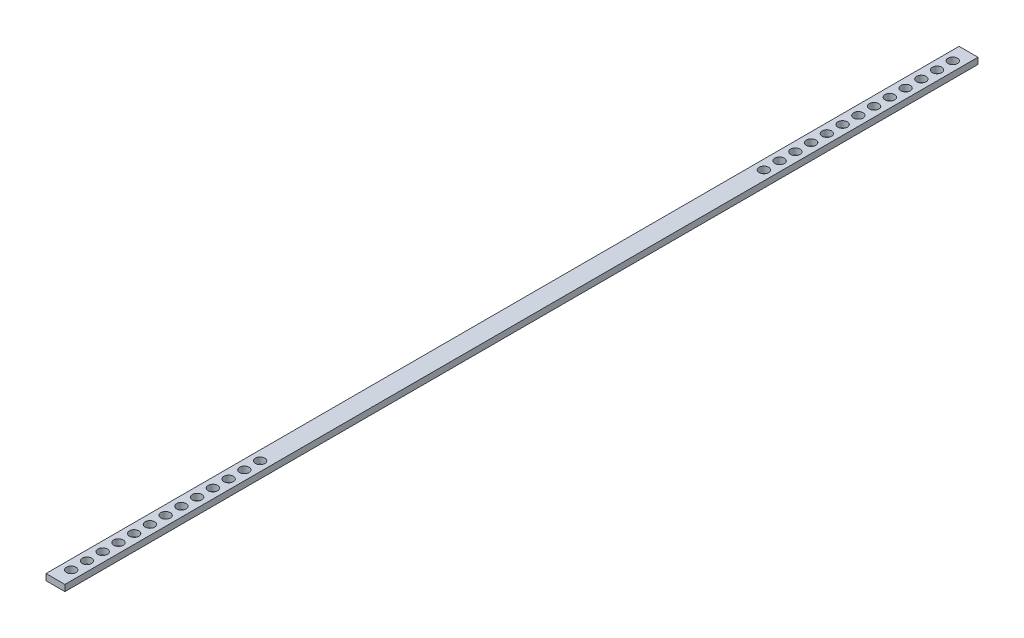
SolidWorks part; units mm, degrees
ref_plane "Ebene vorne" through (0, 0, 0) normal (0, 0, 1) x (1, 0, 0)
ref_plane "Ebene oben" through (0, 0, 0) normal (0, 1, 0) x (1, 0, 0)
ref_plane "Ebene rechts" through (0, 0, 0) normal (1, 0, 0) x (0, 0, -1)
sketch "Skizze1" plane through (0, 0, 0) normal (0, 0, 1) x (1, 0, 0)
  line L1 (0, 0) -> (12, 0)
  line L2 (0, 0) -> (0, 4)
  line L3 (0, 4) -> (12, 4)
  line L4 (12, 0) -> (12, 4)
  dimension "D1" = 12
  dimension "D2" = 4
extrude "Aufsatz-Linear austragen1" add sketch "Skizze1" along normal blind 580
sketch "Skizze2" plane through (0, 4, 0) normal (0, 1, 0) x (1, 0, 0)
  line L0 (0, -290) -> (12, -290) construction
  line L1 (0, -580) -> (0, 0) construction
  line L2 (12, -580) -> (12, 0) construction
  line L3 (6, 0) -> (6, -10) construction
  line L4 (12, 0) -> (0, 0) construction
  line L5 (6, -10) -> (6, -20) construction
  line L6 (6, -20) -> (6, -30) construction
  line L7 (6, -30) -> (6, -40) construction
  line L8 (6, -40) -> (6, -50) construction
  line L9 (6, -50) -> (6, -60) construction
  line L10 (6, -60) -> (6, -70) construction
  line L11 (6, -70) -> (6, -80) construction
  line L12 (6, -80) -> (6, -90) construction
  line L13 (6, -90) -> (6, -100) construction
  line L14 (6, -100) -> (6, -110) construction
  line L15 (6, -110) -> (6, -120) construction
  line L16 (6, -120) -> (6, -130) construction
  line L17 (6, -460) -> (6, -450) construction
  line L18 (6, -470) -> (6, -460) construction
  line L19 (6, -480) -> (6, -470) construction
  line L20 (6, -490) -> (6, -480) construction
  line L21 (6, -500) -> (6, -490) construction
  line L22 (6, -510) -> (6, -500) construction
  line L23 (6, -520) -> (6, -510) construction
  line L24 (6, -530) -> (6, -520) construction
  line L25 (6, -540) -> (6, -530) construction
  line L26 (6, -550) -> (6, -540) construction
  line L27 (6, -560) -> (6, -550) construction
  line L28 (6, -570) -> (6, -560) construction
  line L29 (6, -580) -> (6, -570) construction
  circle A0 centre (6, -10) radius 3
  circle A1 centre (6, -20) radius 3
  circle A2 centre (6, -30) radius 3
  circle A3 centre (6, -40) radius 3
  circle A4 centre (6, -50) radius 3
  circle A5 centre (6, -60) radius 3
  circle A6 centre (6, -70) radius 3
  circle A7 centre (6, -80) radius 3
  circle A8 centre (6, -90) radius 3
  circle A9 centre (6, -100) radius 3
  circle A10 centre (6, -110) radius 3
  circle A11 centre (6, -120) radius 3
  circle A12 centre (6, -130) radius 3
  circle A13 centre (6, -450) radius 3
  circle A14 centre (6, -460) radius 3
  circle A15 centre (6, -470) radius 3
  circle A16 centre (6, -480) radius 3
  circle A17 centre (6, -490) radius 3
  circle A18 centre (6, -500) radius 3
  circle A19 centre (6, -510) radius 3
  circle A20 centre (6, -520) radius 3
  circle A21 centre (6, -530) radius 3
  circle A22 centre (6, -540) radius 3
  circle A23 centre (6, -550) radius 3
  circle A24 centre (6, -560) radius 3
  circle A25 centre (6, -570) radius 3
  dimension "D1" = 6
  dimension "D2" = 10
extrude "Schnitt-Linear austragen1" cut sketch "Skizze2" against normal through all
